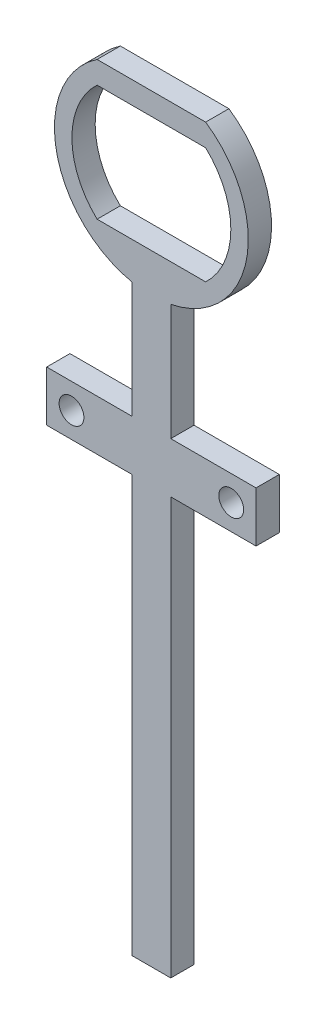
SolidWorks part; units mm, degrees
ref_plane "Front Plane" through (0, 0, 0) normal (0, 0, 1) x (1, 0, 0)
ref_plane "Top Plane" through (0, 0, 0) normal (0, 1, 0) x (1, 0, 0)
ref_plane "Right Plane" through (0, 0, 0) normal (1, 0, 0) x (0, 0, -1)
sketch "Sketch1" plane through (0, 0, 0) normal (0, 0, 1) x (1, 0, 0)
  line L0 (-7, 7.4875) -> (7, 7.4875)
  line L5 (-18.4746, 0) -> (14.4817, 0) construction
  line L6 (-7, -7.4875) -> (7, -7.4875)
  line L7 (-7, 10.3562) -> (7, 10.3562)
  line L8 (0, 0) -> (0, 29.3453) construction
  line L9 (-2.5, -87.4874) -> (2.5, -87.4874)
  line L10 (-2.5, -87.4874) -> (-2.5, -12.2474)
  line L11 (-2.9142, -7.4875) -> (2.3856, -7.4875)
  line L12 (2.5, -87.4874) -> (2.5, -12.2474)
  arc A0 (-7, 7.4875) -> (-7, -7.4875) centre (0, 0) ccw
  arc A1 (7, -7.4875) -> (7, 7.4875) centre (0, 0) ccw
  arc A2 (-7, 10.3562) -> (-2.5, -12.2474) centre (0, 0) ccw
  arc A3 (2.5, -12.2474) -> (7, 10.3562) centre (0, 0) ccw
  point P1 (-0.2997, -67.1413)
  dimension "D1" = 20.5
  dimension "D3" = 25
  dimension "D2" = 14
  dimension "D5" = 80
  dimension "D6" = 5
extrude "Boss-Extrude1" add sketch "Sketch1" along normal blind 3 contours L12 A3 L7 A2 L10 L9 A1 L6 A0 L0
sketch "Sketch3" plane through (0, 0, 0) normal (0, 0, 1) x (1, 0, 0)
  line L0 (0, -46.1586) -> (0, 0.6217) construction
  line L1 (13.5, -27.2474) -> (-13.5, -27.2474)
  line L2 (13.5, -27.2474) -> (13.5, -33.7474)
  line L3 (13.5, -33.7474) -> (-13.5, -33.7474)
  line L4 (-13.5, -27.2474) -> (-13.5, -33.7474)
  line L5 (13.5, -27.2474) -> (-13.5, -33.7474) construction
  line L6 (13.5, -33.7474) -> (-13.5, -27.2474) construction
  circle A0 centre (-10.3, -30.4974) radius 1.6
  circle A1 centre (10.3, -30.4974) radius 1.6
  point P0 (0, -30.4974)
  dimension "D4" = 3.2
  dimension "D5" = 3.2
  dimension "D6" = 3.25
  dimension "D1" = 27
  dimension "D2" = 6.5
  dimension "D3" = 15
extrude "Boss-Extrude2" add sketch "Sketch3" along normal blind 3
